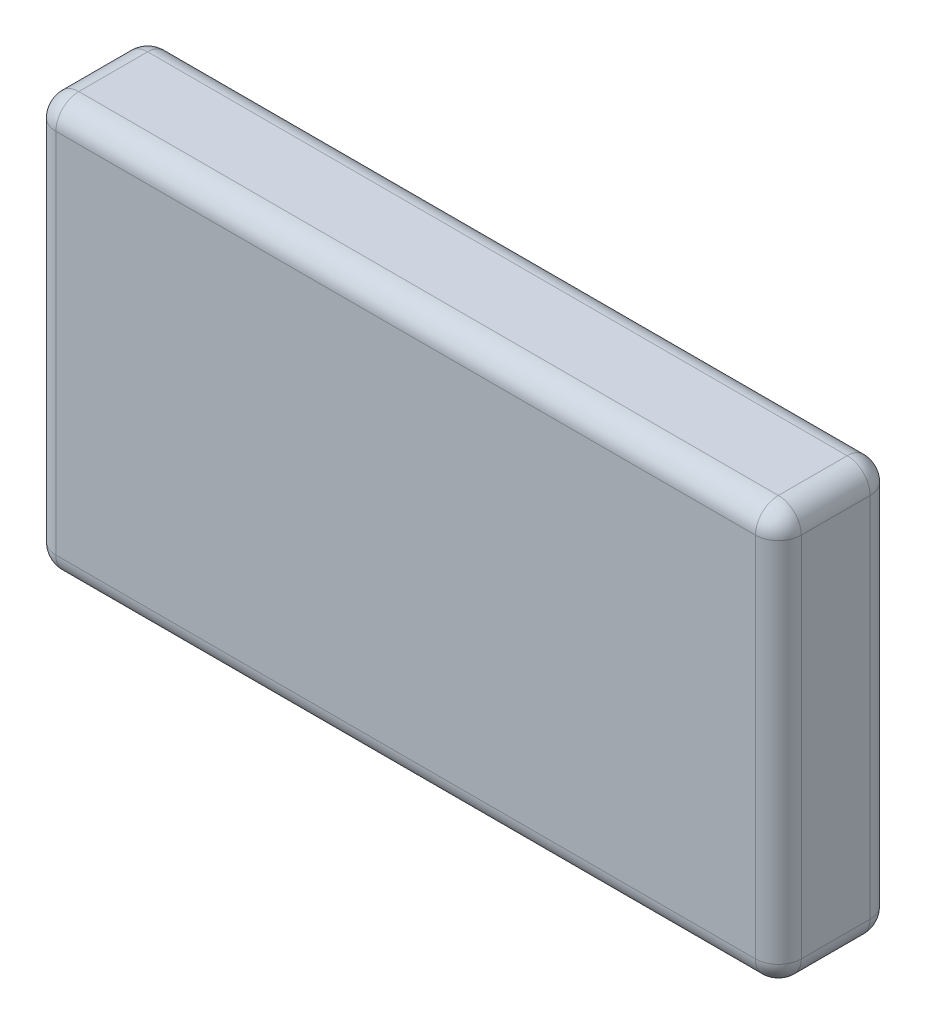
SolidWorks part; units mm, degrees
ref_plane "Спереди" through (0, 0, 0) normal (0, 0, 1) x (1, 0, 0)
ref_plane "Сверху" through (0, 0, 0) normal (0, 1, 0) x (1, 0, 0)
ref_plane "Справа" through (0, 0, 0) normal (1, 0, 0) x (0, 0, -1)
sketch "Эскиз1" plane through (0, 0, 0) normal (0, 0, 1) x (1, 0, 0)
  line L5 (0, 0) -> (65, 0)
  line L6 (0, 0) -> (0, 36)
  line L7 (0, 36) -> (65, 36)
  line L8 (65, 0) -> (65, 36)
  dimension "D1" = 65
  dimension "D2" = 36
extrude "Бобышка-Вытянуть1" add sketch "Эскиз1" along normal blind 10
fillet "Скругление1" radius 2 12 edges at (65, 36, 5) (0, 36, 5) (0, 0, 5) (65, 0, 5) (32.5, 0, 0) (65, 18, 0) (32.5, 36, 0) (0, 18, 0) (32.5, 36, 10) (65, 18, 10) (32.5, 0, 10) (0, 18, 10)
